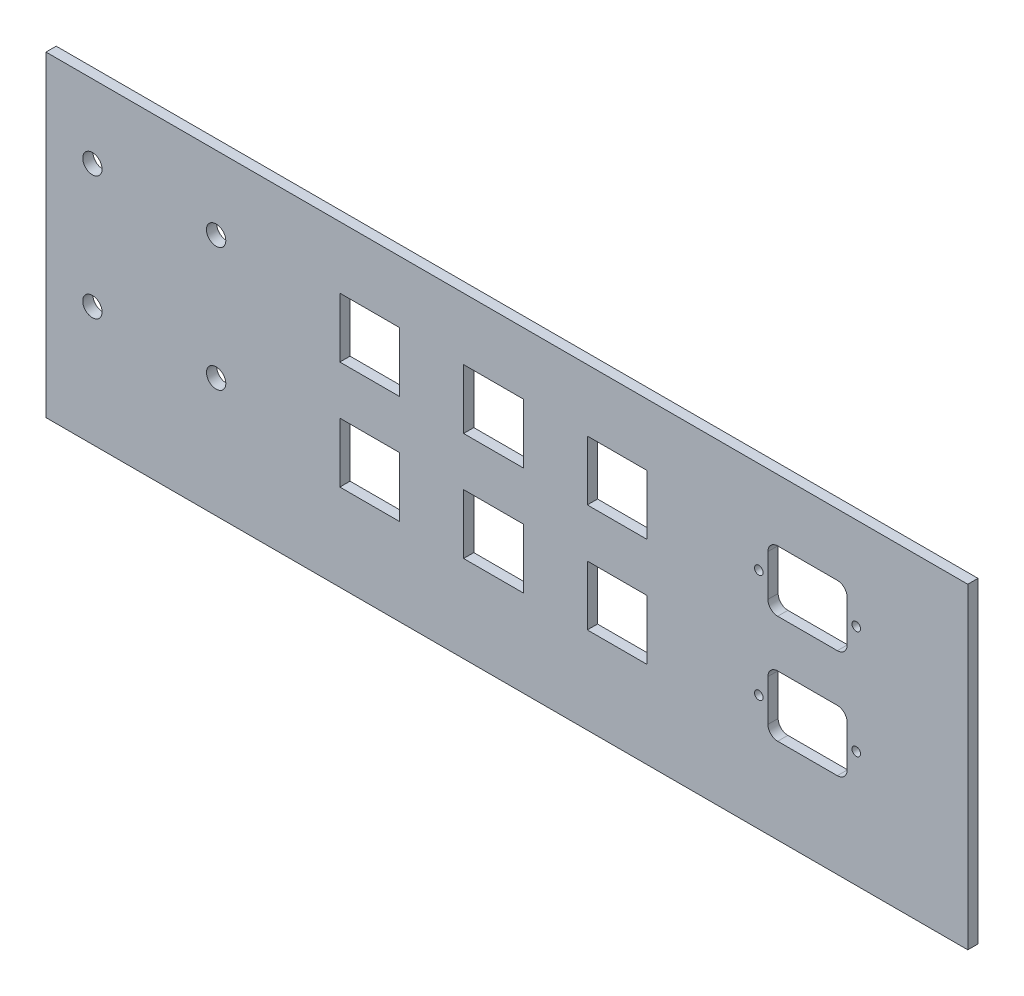
SolidWorks part; units mm, degrees
ref_plane "Front Plane" through (0, 0, 0) normal (0, 0, 1) x (1, 0, 0)
ref_plane "Top Plane" through (0, 0, 0) normal (0, 1, 0) x (1, 0, 0)
ref_plane "Right Plane" through (0, 0, 0) normal (1, 0, 0) x (0, 0, -1)
sketch "Sketch1" plane through (0, 0, 0) normal (0, 0, 1) x (1, 0, 0)
  line L1 (0, 0) -> (378.46, 0)
  line L2 (0, 0) -> (0, 129.9972)
  line L3 (0, 129.9972) -> (378.46, 129.9972)
  line L4 (378.46, 0) -> (378.46, 129.9972)
  dimension "D1" = 378.46
  dimension "D2" = 129.9972
extrude "Boss-Extrude1" add sketch "Sketch1" along normal blind 4.191
sketch "Sketch2" plane through (0, 0, 4.191) normal (0, 0, 1) x (1, 0, 0)
  line L0 (378.46, 129.9972) -> (0, 129.9972) construction
  line L1 (0, 129.9972) -> (0, 0) construction
  point P0 (19.05, 99.8347)
  point P1 (69.85, 99.8347)
  point P2 (19.05, 49.0347)
  point P3 (69.85, 49.0347)
  dimension "D1" = 50.8
  dimension "D2" = 50.8
  dimension "D3" = 30.1625
  dimension "D4" = 19.05
hole_wizard "3/8-16 Tapped Hole1" positions "Sketch4" profile "Sketch3" tap size "3/8-16" standard "ANSI Inch" end condition through all
sketch "Sketch4" plane through (0, 0, 4.191) normal (0, 0, 1) x (1, 0, 0)
  point P0 (19.05, 99.8347)
  point P3 (69.85, 99.8347)
  point P6 (69.85, 49.0347)
  point P9 (19.05, 49.0347)
sketch "Sketch3" plane through (19.05, 99.8347, 4.191) normal (1, 0, 0) x (0, -1, 0)
  line L0 (0, 0) -> (0, 4.191)
  line L1 (0, 4.191) -> (3.9687, 4.191)
  line L2 (3.9687, 4.191) -> (3.9688, 0)
  line L5 (3.9688, 0) -> (0, 0)
  line L11 (0, -6.35) -> (0, 107.95) construction
  dimension "Thru Tap Drill Dia." = 7.9375
  dimension "Thru Tap Drill Depth" = 4.191
cosmetic thread "Hole Thread1" parameters "D2"=9.525
cosmetic thread "Hole Thread2" parameters "D2"=9.525
cosmetic thread "Hole Thread3" parameters "D2"=9.525
cosmetic thread "Hole Thread4" parameters "D2"=9.525
sketch "Sketch5" plane through (0, 0, 4.191) normal (0, 0, 1) x (1, 0, 0)
  line L0 (378.46, 129.9972) -> (0, 129.9972) construction
  line L1 (120.65, 104.5972) -> (145.15, 104.5972)
  line L2 (120.65, 104.5972) -> (120.65, 80.0972)
  line L3 (120.65, 80.0972) -> (145.15, 80.0972)
  line L4 (145.15, 104.5972) -> (145.15, 80.0972)
  line L5 (171.45, 104.5972) -> (171.45, 80.0972)
  line L6 (171.45, 80.0972) -> (195.95, 80.0972)
  line L7 (195.95, 104.5972) -> (195.95, 80.0972)
  line L8 (171.45, 104.5972) -> (195.95, 104.5972)
  line L9 (222.25, 104.5972) -> (222.25, 80.0972)
  line L10 (222.25, 80.0972) -> (246.75, 80.0972)
  line L11 (246.75, 104.5972) -> (246.75, 80.0972)
  line L12 (222.25, 104.5972) -> (246.75, 104.5972)
  line L13 (171.45, 60.1472) -> (171.45, 35.6472)
  line L14 (171.45, 35.6472) -> (195.95, 35.6472)
  line L15 (195.95, 60.1472) -> (195.95, 35.6472)
  line L16 (171.45, 60.1472) -> (195.95, 60.1472)
  line L17 (222.25, 60.1472) -> (222.25, 35.6472)
  line L18 (222.25, 35.6472) -> (246.75, 35.6472)
  line L19 (246.75, 60.1472) -> (246.75, 35.6472)
  line L20 (222.25, 60.1472) -> (246.75, 60.1472)
  line L21 (120.65, 60.1472) -> (120.65, 35.6472)
  line L22 (120.65, 35.6472) -> (145.15, 35.6472)
  line L23 (145.15, 60.1472) -> (145.15, 35.6472)
  line L24 (120.65, 60.1472) -> (145.15, 60.1472)
  dimension "D1" = 24.5
  dimension "D2" = 24.5
  dimension "D3" = 25.4
  dimension "D4" = 50.8
  dimension "D5" = 3
  dimension "D6" = 2
extrude "Cut-Extrude1" cut sketch "Sketch5" against normal up to next
sketch "Sketch7" plane through (0, 0, 4.191) normal (0, 0, 1) x (1, 0, 0)
  line L0 (300.407, 60.1472) -> (324.907, 60.1472)
  line L1 (300.407, 104.5972) -> (324.907, 104.5972)
  line L2 (296.407, 100.5972) -> (296.407, 83.5972)
  line L3 (300.407, 79.5972) -> (324.907, 79.5972)
  line L4 (328.907, 100.5972) -> (328.907, 83.5972)
  line L5 (246.75, 80.0972) -> (246.75, 104.5972) construction
  line L6 (296.407, 56.1472) -> (296.407, 39.1472)
  line L7 (300.407, 35.1472) -> (324.907, 35.1472)
  line L8 (328.907, 56.1472) -> (328.907, 39.1472)
  circle A0 centre (292.657, 92.0972) radius 1.75
  circle A1 centre (332.657, 92.0972) radius 1.75
  arc A2 (296.407, 100.5972) -> (300.407, 104.5972) centre (300.407, 100.5972) cw
  arc A3 (300.407, 79.5972) -> (296.407, 83.5972) centre (300.407, 83.5972) cw
  arc A4 (328.907, 100.5972) -> (324.907, 104.5972) centre (324.907, 100.5972) ccw
  arc A5 (328.907, 83.5972) -> (324.907, 79.5972) centre (324.907, 83.5972) cw
  arc A6 (296.407, 56.1472) -> (300.407, 60.1472) centre (300.407, 56.1472) cw
  arc A7 (300.407, 35.1472) -> (296.407, 39.1472) centre (300.407, 39.1472) cw
  arc A8 (328.907, 39.1472) -> (324.907, 35.1472) centre (324.907, 39.1472) cw
  arc A9 (328.907, 56.1472) -> (324.907, 60.1472) centre (324.907, 56.1472) ccw
  circle A10 centre (332.657, 47.6472) radius 1.75
  circle A11 centre (292.657, 47.6472) radius 1.75
  point P13 (296.407, 104.5972)
  point P16 (296.407, 79.5972)
  point P21 (328.907, 79.5972)
  dimension "D6" = 3.5
  dimension "D7" = 3.5
  dimension "D9" = 4
  dimension "D10" = 4
  dimension "D11" = 4
  dimension "D12" = 4
  dimension "D1" = 32.5
  dimension "D2" = 25
  dimension "D3" = 49.657
  dimension "D4" = 3.75
  dimension "D5" = 3.75
  dimension "D8" = 12.5
  dimension "D13" = 2
extrude "Cut-Extrude2" cut sketch "Sketch7" against normal up to next
